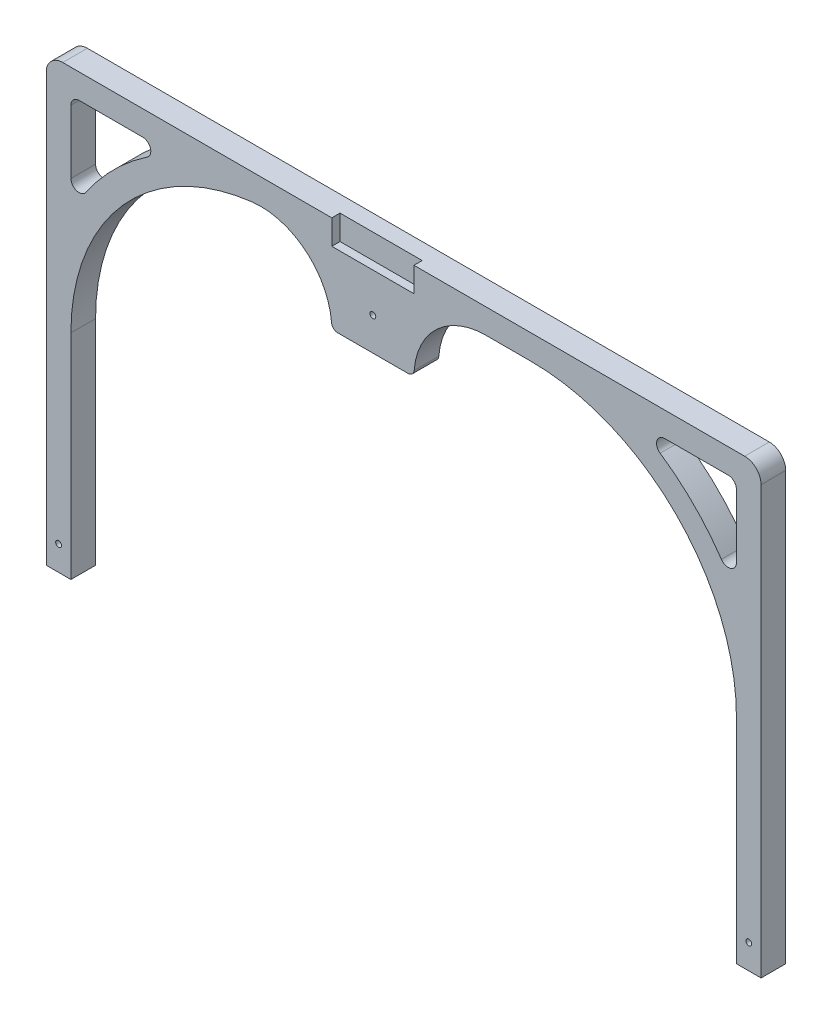
SolidWorks part; units mm, degrees
material "Pine"
ref_plane "Front Plane" through (0, 0, 0) normal (0, 0, 1) x (1, 0, 0)
ref_plane "Top Plane" through (0, 0, 0) normal (0, 1, 0) x (1, 0, 0)
ref_plane "Right Plane" through (0, 0, 0) normal (1, 0, 0) x (0, 0, -1)
sketch "Sketch1" plane through (0, 0, 0) normal (0, 0, 1) x (1, 0, 0)
  line L0 (276.225, 0) -> (276.225, 330.2)
  line L1 (276.225, 0) -> (257.175, 0)
  line L2 (257.175, 0) -> (257.175, 76.2)
  line L3 (276.225, 342.9) -> (-276.225, 342.9) construction
  line L4 (250.825, 323.85) -> (201.7955, 323.85)
  line L5 (257.175, 76.2) -> (257.175, 165.1) construction
  line L6 (263.525, 342.9) -> (-263.525, 342.9)
  line L7 (0, 342.9) -> (0, 0) construction
  line L8 (0, 76.2) -> (276.225, 76.2) construction
  line L9 (98.425, 323.85) -> (-98.425, 323.85)
  line L10 (257.175, 317.5) -> (257.175, 268.4705)
  line L11 (257.175, 245.1705) -> (257.175, 342.9) construction
  line L12 (257.175, 165.1) -> (257.175, 76.2)
  line L13 (-276.225, 0) -> (-276.225, 330.2)
  line L14 (-276.225, 0) -> (-257.175, 0)
  line L15 (-257.175, 0) -> (-257.175, 76.2)
  line L16 (-257.175, 165.1) -> (-257.175, 76.2)
  line L17 (-250.825, 323.85) -> (-201.7955, 323.85)
  line L18 (-257.175, 317.5) -> (-257.175, 268.4705)
  arc A0 (98.425, 323.85) -> (257.175, 165.1) centre (98.425, 165.1) cw
  arc A1 (198.231, 312.2448) -> (245.5698, 264.906) centre (98.425, 165.1) cw
  arc A2 (245.5698, 264.906) -> (257.175, 268.4705) centre (250.825, 268.4705) ccw
  arc A3 (257.175, 317.5) -> (250.825, 323.85) centre (250.825, 317.5) ccw
  arc A4 (198.231, 312.2448) -> (201.7955, 323.85) centre (201.7955, 317.5) cw
  arc A5 (-98.425, 323.85) -> (-257.175, 165.1) centre (-98.425, 165.1) ccw
  arc A6 (-198.231, 312.2448) -> (-201.7955, 323.85) centre (-201.7955, 317.5) ccw
  arc A7 (-257.175, 317.5) -> (-250.825, 323.85) centre (-250.825, 317.5) cw
  arc A8 (-245.5698, 264.906) -> (-257.175, 268.4705) centre (-250.825, 268.4705) cw
  arc A9 (-198.231, 312.2448) -> (-245.5698, 264.906) centre (-98.425, 165.1) ccw
  arc A10 (276.225, 330.2) -> (263.525, 342.9) centre (263.525, 330.2) ccw
  arc A11 (-263.525, 342.9) -> (-276.225, 330.2) centre (-263.525, 330.2) ccw
  point P16 (0, 342.9)
  point P24 (257.175, 323.85)
  point P34 (0, 323.85)
  dimension "D6" = 19.05
  dimension "D8" = 6.35
  dimension "D9" = 12.7
  dimension "D1" = 342.9
  dimension "D2" = 19.05
  dimension "D3" = 552.45
  dimension "D4" = 76.2
  dimension "D5" = 19.05
  dimension "D7" = 88.9
extrude "Boss-Extrude1" add sketch "Sketch1" along normal blind 19.05
sketch "Sketch2" plane through (0, 342.9, 0) normal (0, 1, 0) x (1, 0, 0)
  line L0 (0, 0) -> (0, -19.05) construction
  line L1 (263.525, 0) -> (-263.525, 0) construction
  line L2 (263.525, -19.05) -> (-263.525, -19.05) construction
  line L3 (-23.8125, 0) -> (-23.8125, -19.05) construction
  line L5 (-55.5625, -19.05) -> (7.9375, -19.05)
  line L6 (-55.5625, -19.05) -> (-55.5625, -12.7)
  line L7 (-55.5625, -12.7) -> (7.9375, -12.7)
  line L8 (7.9375, -19.05) -> (7.9375, -12.7)
  point P12 (-23.8125, -19.05)
  dimension "D1" = 23.8125
  dimension "D2" = 63.5
  dimension "D3" = 6.35
extrude "Cut-Extrude1" cut sketch "Sketch2" against normal through all
sketch "Sketch3" plane through (0, 0, 0) normal (0, 0, 1) x (1, 0, 0)
  line L0 (7.9375, 323.85) -> (98.425, 323.85) construction
  line L1 (-55.5625, 323.85) -> (-55.5625, 268.2189) construction
  line L2 (-55.5625, 268.2189) -> (7.9375, 268.2189)
  line L3 (-98.425, 323.85) -> (-55.5625, 323.85) construction
  line L4 (-98.425, 323.85) -> (-55.5625, 323.85)
  line L5 (7.9375, 323.85) -> (63.5686, 323.85)
  line L6 (7.9375, 268.2189) -> (7.9375, 323.85) construction
  line L7 (7.9375, 323.85) -> (-55.5625, 323.85)
  arc A0 (7.9375, 268.2189) -> (63.5686, 323.85) centre (63.5686, 268.2189) cw
  arc A1 (-55.5625, 268.2189) -> (-116.8733, 322.7744) centre (-110.4902, 268.2189) ccw
  arc A2 (-98.425, 323.85) -> (-257.175, 165.1) centre (-98.425, 165.1) ccw construction
  arc A3 (-116.8733, 322.7744) -> (-98.425, 323.85) centre (-98.425, 165.1) cw
  dimension "D1" = 55.6311
extrude "Boss-Extrude3" add sketch "Sketch3" along normal up to surface (19.05 mm away) up to face at (-235.2273, 301.9023, 19.05)
fillet "Fillet1" radius 4.7625 2 edges at (-55.5625, 268.2189, 9.525) (7.9375, 268.2189, 9.525)
hole_wizard "CSK for #8 Flat Head Machine Screw1" positions "Sketch4" profile "Sketch5" countersink size "#8" standard "ANSI Inch"
sketch "Sketch4" plane through (0, 0, 0) normal (0, 0, -1) x (-1, 0, 0)
  line L0 (50.9903, 268.2189) -> (-3.3631, 268.2189) construction
  line L1 (-257.175, 0) -> (-276.225, 0) construction
  line L2 (276.225, 0) -> (257.175, 0) construction
  point P0 (23.8136, 293.6189)
  point P5 (23.8136, 268.2189)
  point P6 (266.7, 19.05)
  point P8 (-266.7, 19.05)
  point P13 (-266.7, 0)
  point P16 (0, 0)
  point P17 (266.7, 0)
  dimension "D1" = 25.4
  dimension "D2" = 19.05
  dimension "D3" = 19.05
sketch "Sketch5" plane through (-23.8136, 293.6189, 0) normal (1, 0, 0) x (0, 1, 0)
  line L0 (0, 0) -> (0, 31.5259)
  line L1 (0, 31.5259) -> (2.2479, 30.1752)
  line L2 (2.2479, 30.1752) -> (2.2479, 2.2645)
  line L3 (2.2479, 2.2645) -> (4.2164, 0)
  line L5 (4.2164, 0) -> (0, 0)
  line L6 (-2.2479, 2.2645) -> (-4.2164, 0) construction
  line L10 (0, 31.5259) -> (-2.2479, 30.1752) construction
  line L11 (0, -6.35) -> (0, 107.95) construction
  dimension "Hole Dia." = 4.4958
  dimension "Hole Depth" = 30.1752
  dimension "Near C'Sink Dia." = 8.4328
  dimension "Near C'Sink Angle" = 82
  dimension "Drill Angle" = 118
